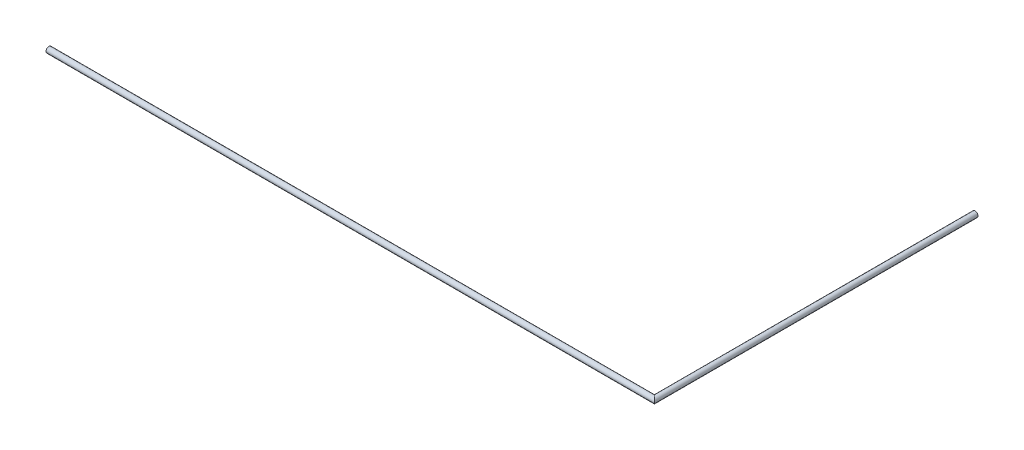
SolidWorks part; units mm, degrees
ref_plane "Alzado" through (0, 0, 0) normal (0, 0, 1) x (1, 0, 0)
ref_plane "Planta" through (0, 0, 0) normal (0, 1, 0) x (1, 0, 0)
ref_plane "Vista lateral" through (0, 0, 0) normal (1, 0, 0) x (0, 0, -1)
sketch "Croquis1" plane through (0, 0, 0) normal (0, 0, 1) x (1, 0, 0)
  circle A0 centre (0, 0) radius 12.7
  dimension "D1" = 25.4
extrude "Saliente-Extruir1" add sketch "Croquis1" along normal blind 30
sketch3d "Croquis3D1"
  line L0 (0, 0, 30) -> (0, 0, 1430)
  line L1 (0, 0, 30) -> (0, 0, 0) construction
  line L2 (0, 0, 1430) -> (-2700, 0, 1430)
  dimension "D1" = 1400
  dimension "D2" = 2700
sketch "Croquis2" plane through (0, 0, 30) normal (0, 0, 1) x (1, 0, 0)
  circle A0 centre (0, 0) radius 12.7
  dimension "D1" = 25.4
sweep "Barrer1" add profiles "Croquis2" path "Croquis3D1"
